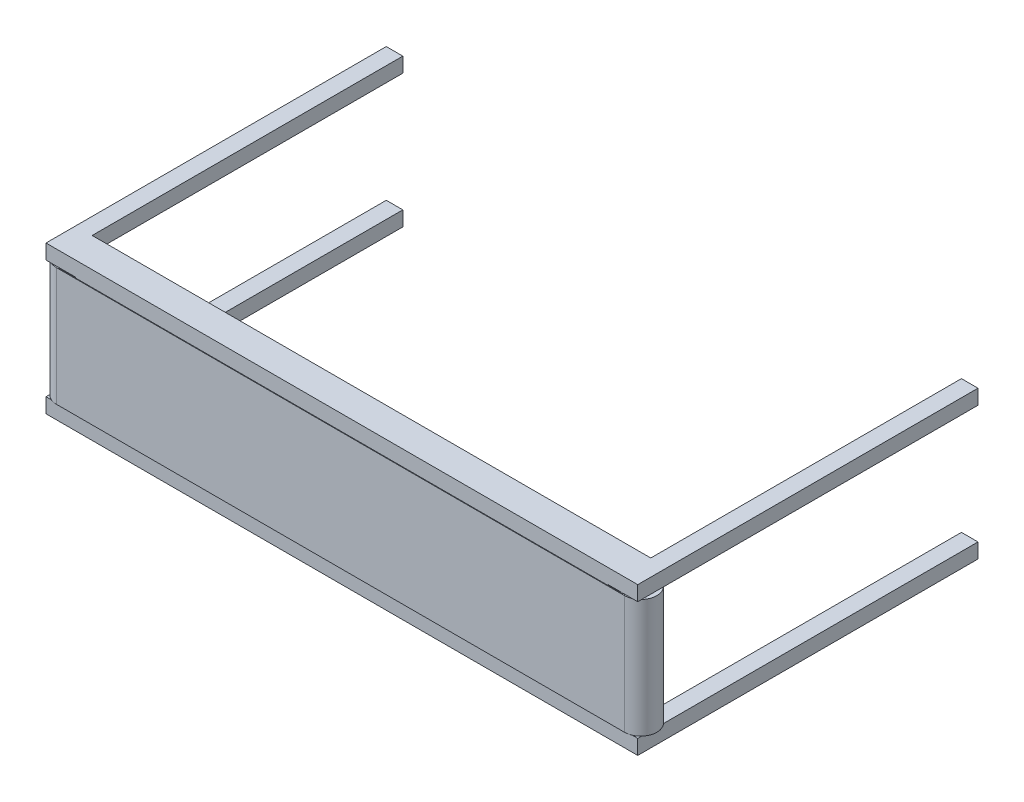
SolidWorks part; units mm, degrees
ref_plane "Front Plane" through (0, 0, 0) normal (0, 0, 1) x (1, 0, 0)
ref_plane "Top Plane" through (0, 0, 0) normal (0, 1, 0) x (1, 0, 0)
ref_plane "Right Plane" through (0, 0, 0) normal (1, 0, 0) x (0, 0, -1)
sketch "Sketch1" plane through (0, 0, 0) normal (0, 0, 1) x (1, 0, 0)
  line L0 (-1000, 200) -> (-900, 200)
  line L1 (1000, -250) -> (-1000, -250)
  line L2 (1000, -250) -> (1000, -200)
  line L3 (1000, 250) -> (-1000, 250)
  line L4 (-1000, -250) -> (-1000, -200)
  line L5 (1000, -250) -> (-1000, 250) construction
  line L6 (1000, 250) -> (-1000, -250) construction
  line L7 (-900, 200) -> (-900, -200)
  line L8 (-900, -200) -> (-1000, -200)
  line L9 (-1000, 200) -> (-1000, 250)
  line L10 (0, 250) -> (0, -250) construction
  line L11 (900, -200) -> (1000, -200)
  line L12 (900, 200) -> (900, -200)
  line L13 (1000, 200) -> (900, 200)
  line L14 (1000, 200) -> (1000, 250)
  point P0 (0, 0)
  dimension "D1" = 500
  dimension "D2" = 2000
  dimension "D3" = 100
  dimension "D4" = 50
  dimension "D5" = 50
extrude "Boss-Extrude1" add sketch "Sketch1" along normal blind 100
sketch "Sketch2" plane through (0, 200, 0) normal (0, -1, 0) x (1, 0, 0)
  line L0 (1000, 100) -> (1000, 0) construction
  circle A0 centre (960, 50) radius 52.5
  dimension "D1" = 105
  dimension "D2" = 40
extrude "Boss-Extrude2" add sketch "Sketch2" along normal blind 400
mirror "Mirror1" about plane through (0, 0, 0) normal (1, 0, 0) of "Boss-Extrude2"
sketch "Sketch3" plane through (0, -200, 0) normal (0, -1, 0) x (1, 0, 0)
  line L0 (-960, 102.5) -> (960, 102.5)
  line L2 (960, -2.5) -> (-1001.3076, 17.5974)
  line L3 (959.9897, -4.5) -> (-1002.2775, 15.6072)
  line L4 (-960, 104.5) -> (960, 104.5)
  arc A0 (-960, 102.5) -> (-1001.3076, 17.5974) centre (-960, 50) ccw
  arc A1 (960, -2.5) -> (960, 102.5) centre (960, 50) ccw
  arc A2 (-960, 104.5) -> (-1002.2775, 15.6072) centre (-960, 50) ccw
  arc A3 (959.9897, -4.5) -> (960, 104.5) centre (960, 50) ccw
  dimension "D1" = 105
  dimension "D2" = 105
  dimension "D3" = 2
extrude "Boss-Extrude3" add sketch "Sketch3" against normal blind 400
sketch "Sketch4" plane through (0, 0, 0) normal (0, 0, -1) x (-1, 0, 0)
  line L0 (0, 250) -> (0, 0) construction
  line L1 (-1000, 250) -> (-943.9922, 250)
  line L2 (-1000, 250) -> (-1000, 200)
  line L3 (-1000, 200) -> (-943.9922, 200)
  line L4 (-943.9922, 250) -> (-943.9922, 200)
  line L5 (-1000, 250) -> (1000, 250) construction
  line L6 (0, 0) -> (1014.5, 0) construction
  line L7 (1014.5, -200) -> (1014.5, 200) construction
  line L8 (1000, 200) -> (943.9922, 200)
  line L9 (943.9922, 250) -> (943.9922, 200)
  line L10 (1000, 250) -> (943.9922, 250)
  line L11 (1000, 250) -> (1000, 200)
  line L12 (1000, -250) -> (1000, -200)
  line L13 (1000, -250) -> (943.9922, -250)
  line L14 (943.9922, -250) -> (943.9922, -200)
  line L15 (1000, -200) -> (943.9922, -200)
  line L16 (-1000, -200) -> (-943.9922, -200)
  line L17 (-943.9922, -250) -> (-943.9922, -200)
  line L18 (-1000, -250) -> (-943.9922, -250)
  line L19 (-1000, -250) -> (-1000, -200)
  dimension "D1" = 56.0078
extrude "Boss-Extrude4" add sketch "Sketch4" along normal blind 1050
